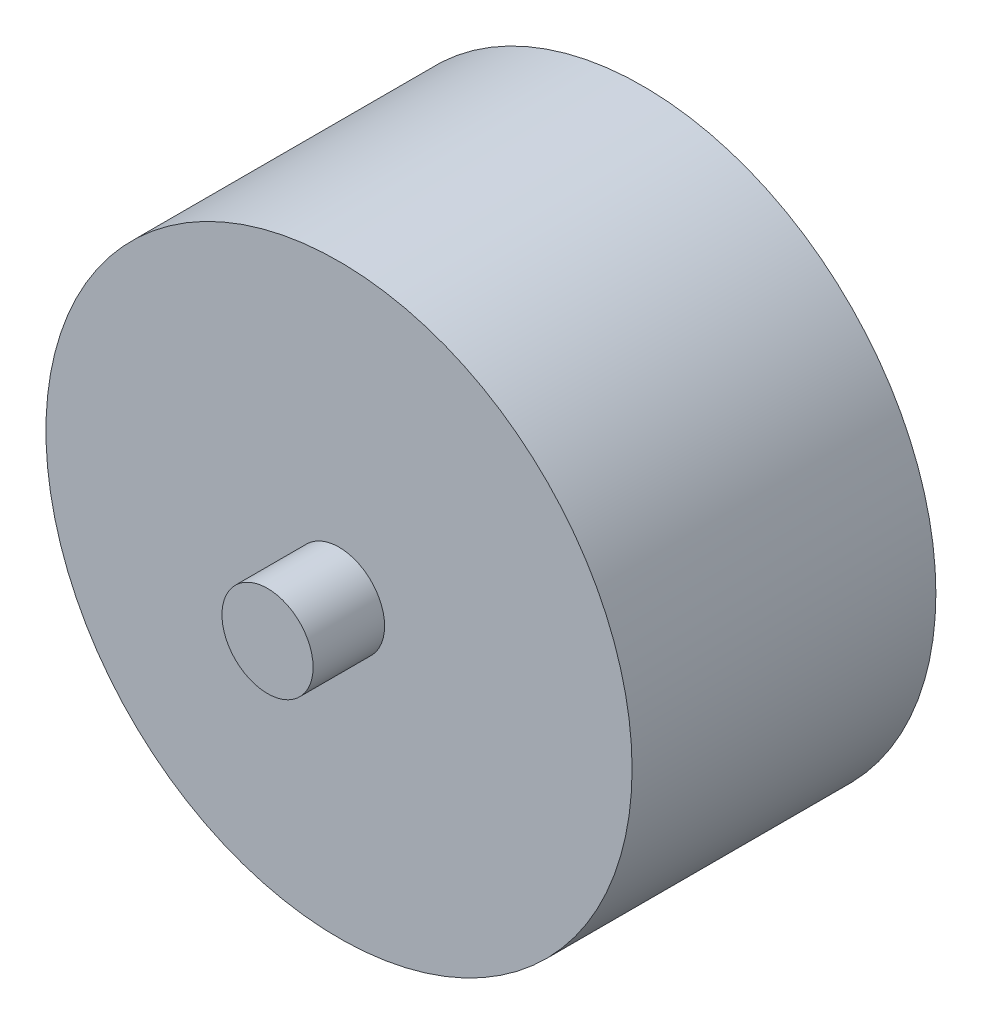
SolidWorks part; units mm, degrees
ref_plane "前视基准面" through (0, 0, 0) normal (0, 0, 1) x (1, 0, 0)
ref_plane "上视基准面" through (0, 0, 0) normal (0, 1, 0) x (1, 0, 0)
ref_plane "右视基准面" through (0, 0, 0) normal (1, 0, 0) x (0, 0, -1)
other "Configuration Table"
sketch "草图1" plane through (0, 0, 0) normal (0, 0, 1) x (1, 0, 0)
  circle A0 centre (0, 0) radius 16.4
  dimension "D1" = 32.8
extrude "凸台-拉伸1" add sketch "草图1" along normal blind 17
sketch "草图2" plane through (0, 0, 17) normal (0, 0, 1) x (1, 0, 0)
  circle A0 centre (0, 0) radius 2.55
  dimension "D1" = 5.1
extrude "凸台-拉伸2" add sketch "草图2" along normal blind 4
sketch "草图3" plane through (0, 0, 0) normal (0, 0, -1) x (-1, 0, 0)
  circle A0 centre (0, 0) radius 10.075
  dimension "D1" = 20.15
extrude "凸台-拉伸3" add sketch "草图3" along normal blind 2 separate body
sketch "草图7" plane through (0, 0, -2) normal (0, 0, -1) x (-1, 0, 0)
  line L0 (0, 0) -> (0, 8) construction
  line L1 (0, 0) -> (8, 0) construction
  line L2 (0, 0) -> (0, -8) construction
  line L3 (0, 0) -> (-8, 0) construction
  circle A0 centre (0, 8) radius 1.05
  circle A1 centre (8, 0) radius 1.05
  circle A2 centre (0, -8) radius 1.05
  circle A3 centre (-8, 0) radius 1.05
  point P13 (0, 0)
  dimension "D1" = 4
extrude "切除-拉伸3" cut sketch "草图7" against normal blind 10 contours A0 | A1 | A2 | A3
